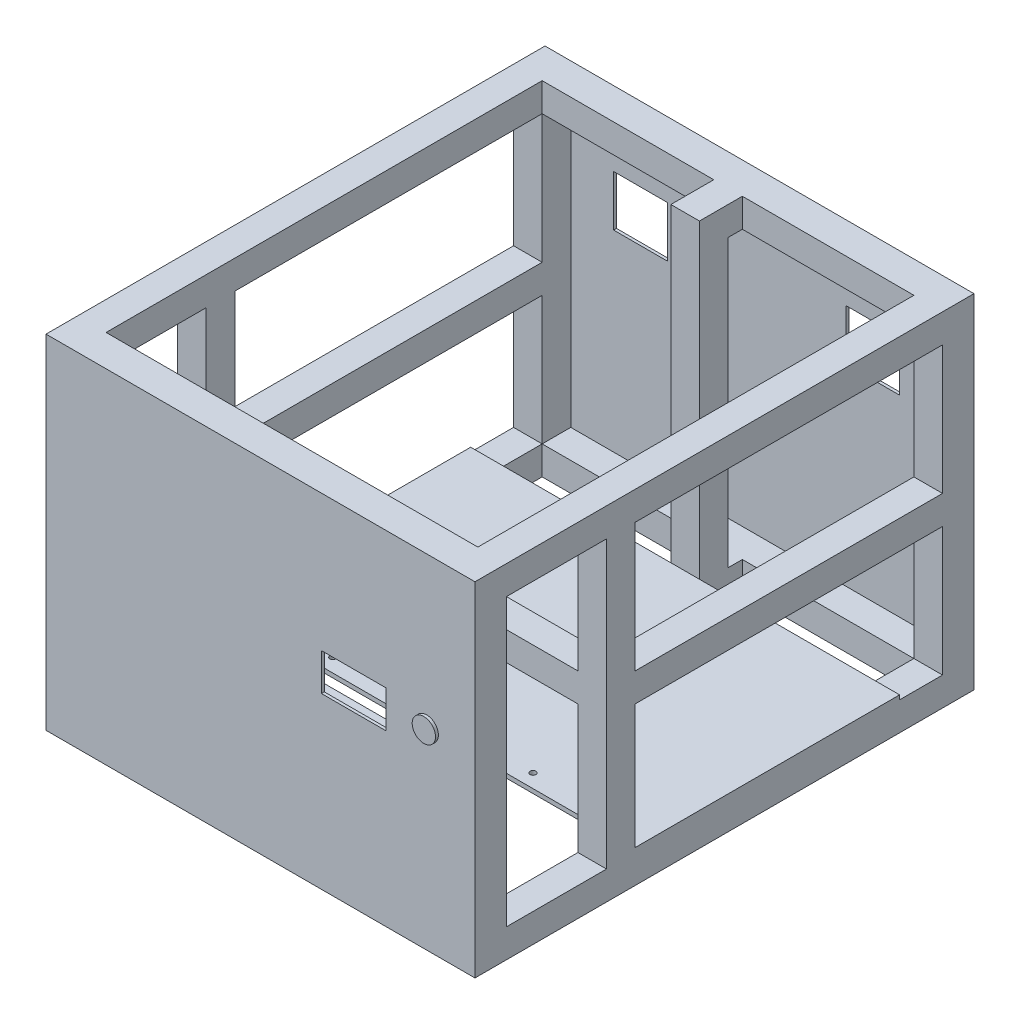
SolidWorks part; units mm, degrees
ref_plane "前视基准面" through (0, 0, 0) normal (0, 0, 1) x (1, 0, 0)
ref_plane "上视基准面" through (0, 0, 0) normal (0, 1, 0) x (1, 0, 0)
ref_plane "右视基准面" through (0, 0, 0) normal (1, 0, 0) x (0, 0, -1)
sketch "草图1" plane through (0, 0, 0) normal (0, 1, 0) x (1, 0, 0)
  line L1 (-150, 172.5) -> (150, 172.5)
  line L2 (-150, 172.5) -> (-150, -172.5)
  line L3 (-150, -172.5) -> (150, -172.5)
  line L4 (150, 172.5) -> (150, -172.5)
  line L5 (-150, 172.5) -> (150, -172.5) construction
  line L6 (-150, -172.5) -> (150, 172.5) construction
  point P0 (0, 0)
  dimension "D1" = 300
  dimension "D2" = 345
extrude "凸台-拉伸1" add sketch "草图1" along normal blind 240
sketch "草图2" plane through (0, 240, 0) normal (0, 1, 0) x (1, 0, 0)
  line L1 (-130, 152.5) -> (130, 152.5)
  line L2 (-130, 152.5) -> (-130, -152.5)
  line L3 (-130, -152.5) -> (130, -152.5)
  line L4 (130, 152.5) -> (130, -152.5)
  line L5 (-130, 152.5) -> (130, -152.5) construction
  line L6 (-130, -152.5) -> (130, 152.5) construction
  point P0 (0, 0)
  dimension "D1" = 260
  dimension "D2" = 305
extrude "切除-拉伸1" cut sketch "草图2" against normal blind 240
sketch "草图3" plane through (0, 0, 172.5) normal (0, 0, 1) x (1, 0, 0)
  line L0 (-150, 240) -> (-150, 0) construction
  line L1 (-130, 220) -> (130, 220)
  line L2 (-130, 220) -> (-130, 20)
  line L3 (-130, 20) -> (130, 20)
  line L4 (130, 220) -> (130, 20)
  line L5 (-150, 0) -> (150, 0) construction
  dimension "D1" = 200
  dimension "D2" = 260
  dimension "D3" = 20
  dimension "D4" = 20
extrude "切除-拉伸2" cut sketch "草图3" against normal blind 345
sketch "草图4" plane through (-150, 0, 0) normal (-1, 0, 0) x (0, 0, 1)
  line L0 (172.5, 0) -> (-172.5, 0) construction
  line L1 (152.5, 220) -> (-152.5, 220)
  line L2 (152.5, 220) -> (152.5, 20)
  line L3 (152.5, 20) -> (-152.5, 20)
  line L4 (-152.5, 220) -> (-152.5, 20)
  line L5 (-172.5, 240) -> (-172.5, 0) construction
  dimension "D1" = 305
  dimension "D2" = 200
  dimension "D3" = 20
  dimension "D4" = 20
extrude "切除-拉伸3" cut sketch "草图4" against normal blind 345
sketch "草图5" plane through (150, 0, 0) normal (1, 0, 0) x (0, 0, -1)
  line L0 (-172.5, 240) -> (172.5, 240) construction
  line L1 (-82.5, 240) -> (-62.5, 240)
  line L2 (-82.5, 240) -> (-82.5, 0)
  line L3 (-82.5, 0) -> (-62.5, 0)
  line L4 (-62.5, 240) -> (-62.5, 0)
  line L5 (-172.5, 0) -> (172.5, 0) construction
  line L6 (-172.5, 240) -> (-172.5, 0) construction
  dimension "D1" = 20
  dimension "D2" = 90
extrude "凸台-拉伸2" add sketch "草图5" against normal blind 20
sketch "草图6" plane through (-150, 0, 0) normal (-1, 0, 0) x (0, 0, 1)
  line L0 (-172.5, 240) -> (172.5, 240) construction
  line L1 (82.5, 240) -> (62.5, 240)
  line L2 (82.5, 240) -> (82.5, 0)
  line L3 (82.5, 0) -> (62.5, 0)
  line L4 (62.5, 240) -> (62.5, 0)
  line L5 (-172.5, 0) -> (172.5, 0) construction
  line L6 (172.5, 240) -> (172.5, 0) construction
  dimension "D1" = 20
  dimension "D2" = 90
extrude "凸台-拉伸3" add sketch "草图6" against normal blind 20
sketch "草图10" plane through (0, 0, -172.5) normal (0, 0, -1) x (-1, 0, 0)
  line L0 (-150, 240) -> (150, 240) construction
  line L1 (-10, 240) -> (10, 240)
  line L2 (-10, 240) -> (-10, 0)
  line L3 (-10, 0) -> (10, 0)
  line L4 (10, 240) -> (10, 0)
  line L5 (-150, 0) -> (150, 0) construction
  line L6 (150, 240) -> (150, 0) construction
  dimension "D1" = 20
  dimension "D2" = 140
extrude "凸台-拉伸7" add sketch "草图10" against normal blind 50
sketch "草图11" plane through (0, 0, -172.5) normal (0, 0, -1) x (-1, 0, 0)
  line L1 (-10, 220) -> (10, 220)
  line L2 (-10, 220) -> (-10, 20)
  line L3 (-10, 20) -> (10, 20)
  line L4 (10, 220) -> (10, 20)
extrude "切除-拉伸4" cut sketch "草图11" against normal blind 50
sketch "草图12" plane through (0, 240, 0) normal (0, 1, 0) x (1, 0, 0)
  line L0 (10, 122.5) -> (10, 152.5) construction
  line L1 (-10, 122.5) -> (10, 122.5)
  line L2 (-10, 122.5) -> (-10, 142.5)
  line L3 (-10, 142.5) -> (10, 142.5)
  line L4 (10, 122.5) -> (10, 142.5)
  dimension "D1" = 20
extrude "凸台-拉伸8" add sketch "草图12" against normal blind 240
sketch "草图13" plane through (150, 0, 0) normal (1, 0, 0) x (0, 0, -1)
  line L0 (-82.5, 220) -> (-82.5, 20) construction
  line L1 (-82.5, 130) -> (-62.5, 130)
  line L2 (-82.5, 130) -> (-82.5, 110)
  line L3 (-82.5, 110) -> (-62.5, 110)
  line L4 (-62.5, 130) -> (-62.5, 110)
  line L5 (-62.5, 20) -> (-62.5, 220) construction
  line L6 (-172.5, 240) -> (172.5, 240) construction
  dimension "D1" = 20
  dimension "D2" = 110
extrude "凸台-拉伸9" add sketch "草图13" against normal blind 300
sketch "草图14" plane through (0, 20, 0) normal (0, 1, 0) x (1, 0, 0)
  line L0 (150, 152.5) -> (150, -62.5) construction
  line L1 (-150, 122.5) -> (150, 122.5)
  line L2 (-150, 122.5) -> (-150, -62.5)
  line L3 (-150, -62.5) -> (150, -62.5)
  line L4 (150, 122.5) -> (150, -62.5)
  line L5 (-150, -62.5) -> (-130, -62.5) construction
  dimension "D1" = 300
  dimension "D2" = 185
  dimension "D3" = 0
  dimension "D4" = 0
extrude "凸台-拉伸10" add sketch "草图14" along normal blind 3
sketch "草图15" plane through (0, 23, 0) normal (0, 1, 0) x (1, 0, 0)
  circle A0 centre (-70.9471, -52.987) radius 2.05
  circle A1 centre (-0.9471, -52.987) radius 2.05
  circle A2 centre (69.0529, -52.987) radius 2.05
  dimension "D1" = 4.1
  dimension "D2" = 3
extrude "切除-拉伸5" cut sketch "草图15" against normal blind 3
sketch "草图16" plane through (150, 0, 0) normal (1, 0, 0) x (0, 0, -1)
  line L0 (-62.5, 23) -> (-62.5, 220) construction
  line L1 (-62.5, 130) -> (152.5, 130)
  line L2 (-62.5, 130) -> (-62.5, 110)
  line L3 (-62.5, 110) -> (152.5, 110)
  line L4 (152.5, 130) -> (152.5, 110)
  line L5 (152.5, 220) -> (152.5, 20) construction
  line L6 (-172.5, 0) -> (172.5, 0) construction
  dimension "D1" = 20
  dimension "D2" = 110
extrude "凸台-拉伸11" add sketch "草图16" against normal blind 20
sketch "草图17" plane through (-150, 0, 0) normal (-1, 0, 0) x (0, 0, 1)
  line L0 (-152.5, 220) -> (-152.5, 20) construction
  line L1 (-152.5, 130) -> (62.5, 130)
  line L2 (-152.5, 130) -> (-152.5, 110)
  line L3 (-152.5, 110) -> (62.5, 110)
  line L4 (62.5, 130) -> (62.5, 110)
  line L5 (62.5, 220) -> (62.5, 23) construction
  line L6 (-172.5, 0) -> (172.5, 0) construction
  dimension "D1" = 20
  dimension "D2" = 110
extrude "凸台-拉伸12" add sketch "草图17" against normal blind 20
sketch "草图18" plane through (0, 0, 172.5) normal (0, 0, 1) x (1, 0, 0)
  line L1 (-150, 240) -> (150, 240)
  line L2 (-150, 240) -> (-150, 0)
  line L3 (-150, 0) -> (150, 0)
  line L4 (150, 240) -> (150, 0)
extrude "凸台-拉伸13" add sketch "草图18" along normal blind 2
sketch "草图20" plane through (0, 0, -172.5) normal (0, 0, -1) x (-1, 0, 0)
  line L1 (-150, 240) -> (150, 240)
  line L2 (-150, 240) -> (-150, 0)
  line L3 (-150, 0) -> (150, 0)
  line L4 (150, 240) -> (150, 0)
extrude "凸台-拉伸14" add sketch "草图20" along normal blind 2
sketch "草图21" plane through (0, 0, 174.5) normal (0, 0, 1) x (1, 0, 0)
  circle A0 centre (116.2493, 134.3333) radius 8.165
extrude "凸台-拉伸15" add sketch "草图21" along normal blind 2
sketch "草图22" plane through (0, 0, 174.5) normal (0, 0, 1) x (1, 0, 0)
  line L0 (-150, 240) -> (-150, 0) construction
  line L1 (-150, 188.6671) -> (150, 188.6671)
  line L2 (-150, 188.6671) -> (-150, 168.6671)
  line L3 (-150, 168.6671) -> (150, 168.6671)
  line L4 (150, 188.6671) -> (150, 168.6671)
  line L5 (150, 0) -> (150, 240) construction
  line L7 (-150, 103.6671) -> (150, 103.6671)
  line L8 (-150, 103.6671) -> (-150, 83.6671)
  line L9 (-150, 83.6671) -> (150, 83.6671)
  line L10 (150, 103.6671) -> (150, 83.6671)
  dimension "D1" = 20
  dimension "D2" = 20
  dimension "D3" = 85
sketch "草图23" plane through (0, 0, 174.5) normal (0, 0, 1) x (1, 0, 0)
extrude "凸台-拉伸16" add sketch "草图22" against normal blind 22
sketch "草图24" plane through (0, 0, 174.5) normal (0, 0, 1) x (1, 0, 0)
  line L1 (42.6149, 144.6144) -> (87.6149, 144.6144)
  line L2 (42.6149, 144.6144) -> (42.6149, 118.6144)
  line L3 (42.6149, 118.6144) -> (87.6149, 118.6144)
  line L4 (87.6149, 144.6144) -> (87.6149, 118.6144)
  dimension "D1" = 45
  dimension "D2" = 26
extrude "切除-拉伸6" cut sketch "草图24" against normal blind 2
sketch "草图25" plane through (0, 0, -174.5) normal (0, 0, -1) x (-1, 0, 0)
  line L0 (150, 240) -> (-150, 240) construction
  line L1 (62.5, 190) -> (100, 190)
  line L2 (62.5, 190) -> (62.5, 154.5)
  line L3 (62.5, 154.5) -> (100, 154.5)
  line L4 (100, 190) -> (100, 154.5)
  line L5 (150, 0) -> (150, 240) construction
  dimension "D1" = 37.5
  dimension "D2" = 35.5
  dimension "D3" = 50
  dimension "D4" = 50
extrude "切除-拉伸7" cut sketch "草图25" against normal blind 2
sketch "草图26" plane through (0, 0, -174.5) normal (0, 0, -1) x (-1, 0, 0)
  line L0 (150, 240) -> (-150, 240) construction
  line L1 (-100, 190) -> (-62.5, 190)
  line L2 (-100, 190) -> (-100, 154.5)
  line L3 (-100, 154.5) -> (-62.5, 154.5)
  line L4 (-62.5, 190) -> (-62.5, 154.5)
  line L5 (-150, 240) -> (-150, 0) construction
  dimension "D1" = 37.5
  dimension "D2" = 35.5
  dimension "D3" = 50
  dimension "D4" = 50
extrude "切除-拉伸8" cut sketch "草图26" against normal blind 2
sketch "草图27" plane through (0, 0, -174.5) normal (0, 0, -1) x (-1, 0, 0)
  circle A0 centre (-104.6574, 57.0502) radius 4
  circle A1 centre (-64.6574, 57.0502) radius 4
  dimension "D1" = 8
  dimension "D2" = 2
extrude "凸台-拉伸17" add sketch "草图27" along normal blind 10
sketch "草图28" plane through (0, 0, -174.5) normal (0, 0, -1) x (-1, 0, 0)
  circle A0 centre (54.1619, 57.8393) radius 4
  circle A1 centre (94.1619, 57.8393) radius 4
  dimension "D1" = 8
  dimension "D2" = 2
extrude "凸台-拉伸18" add sketch "草图28" along normal blind 10
